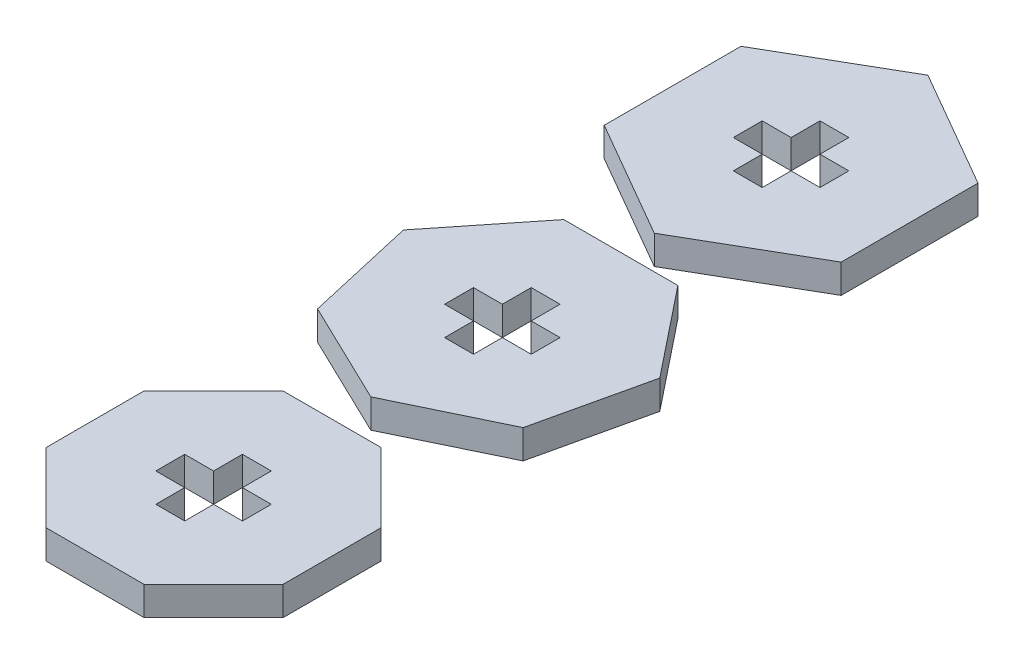
SolidWorks part; units mm, degrees
ref_plane "Front Plane" through (0, 0, 0) normal (0, 0, 1) x (1, 0, 0)
ref_plane "Top Plane" through (0, 0, 0) normal (0, 1, 0) x (1, 0, 0)
ref_plane "Right Plane" through (0, 0, 0) normal (1, 0, 0) x (0, 0, -1)
sketch "Sketch1" plane through (0, 0, 0) normal (0, 1, 0) x (1, 0, 0)
  line L0 (-20.9755, 38.5205) -> (-20.9755, -115.5968) construction
  line L1 (-20.9755, 38.5205) -> (-20.9755, 68.0435) construction
  line L2 (-20.9755, 14.4513) -> (-0.131, 26.4859)
  line L3 (-0.131, 26.4859) -> (-0.131, 50.5551)
  line L4 (-0.131, 50.5551) -> (-20.9755, 62.5897)
  line L5 (-20.9755, 62.5897) -> (-41.82, 50.5551)
  line L6 (-41.82, 50.5551) -> (-41.82, 26.4859)
  line L7 (-41.82, 26.4859) -> (-20.9755, 14.4513)
  line L8 (-20.9755, -35.4152) -> (-2.8873, -26.7044)
  line L9 (-2.8873, -26.7044) -> (1.5801, -7.1313)
  line L10 (1.5801, -7.1313) -> (-10.9373, 8.565)
  line L11 (-10.9373, 8.565) -> (-31.0137, 8.565)
  line L12 (-31.0137, 8.565) -> (-43.5311, -7.1313)
  line L13 (-43.5311, -7.1313) -> (-39.0637, -26.7044)
  line L14 (-39.0637, -26.7044) -> (-20.9755, -35.4152)
  line L15 (-12.3415, -42.235) -> (-29.6096, -42.235)
  line L16 (-29.6096, -42.235) -> (-41.82, -54.4454)
  line L17 (-41.82, -54.4454) -> (-41.82, -71.7136)
  line L18 (-41.82, -71.7136) -> (-29.6096, -83.924)
  line L19 (-29.6096, -83.924) -> (-12.3415, -83.924)
  line L20 (-12.3415, -83.924) -> (-0.131, -71.7136)
  line L21 (-0.131, -71.7136) -> (-0.131, -54.4454)
  line L22 (-0.131, -54.4454) -> (-12.3415, -42.235)
  line L23 (-20.9755, 46.1405) -> (-18.4355, 46.1405)
  line L24 (-130.3452, 38.5205) -> (97.3734, 38.5205) construction
  line L25 (97.3734, -12.2795) -> (-130.3452, -12.2795) construction
  line L26 (-130.3452, -63.0795) -> (97.3734, -63.0795) construction
  line L27 (-18.4355, 46.1405) -> (-18.4355, 41.0605)
  line L28 (-18.4355, 41.0605) -> (-13.3555, 41.0605)
  line L29 (-13.3555, 41.0605) -> (-13.3555, 38.5205)
  line L30 (-13.3555, 38.5205) -> (-13.3555, 35.9805)
  line L31 (-13.3555, 35.9805) -> (-18.4355, 35.9805)
  line L32 (-18.4355, 35.9805) -> (-18.4355, 30.9005)
  line L33 (-18.4355, 30.9005) -> (-20.9755, 30.9005)
  line L34 (-20.9755, 30.9005) -> (-23.5155, 30.9005)
  line L35 (-23.5155, 30.9005) -> (-23.5155, 35.9805)
  line L36 (-23.5155, 35.9805) -> (-28.5955, 35.9805)
  line L37 (-28.5955, 35.9805) -> (-28.5955, 38.5205)
  line L38 (-28.5955, 38.5205) -> (-28.5955, 41.0605)
  line L39 (-28.5955, 41.0605) -> (-23.5155, 41.0605)
  line L40 (-23.5155, 41.0605) -> (-23.5155, 46.1405)
  line L41 (-23.5155, 46.1405) -> (-20.9755, 46.1405)
  line L42 (-23.5155, -14.8195) -> (-28.5955, -14.8195)
  line L43 (-20.9755, -4.6595) -> (-18.4355, -4.6595)
  line L44 (-18.4355, -19.8995) -> (-20.9755, -19.8995)
  line L45 (-23.5155, -9.7395) -> (-23.5155, -4.6595)
  line L46 (-13.3555, -12.2795) -> (-13.3555, -14.8195)
  line L47 (-28.5955, -14.8195) -> (-28.5955, -12.2795)
  line L48 (-18.4355, -4.6595) -> (-18.4355, -9.7395)
  line L49 (-20.9755, -19.8995) -> (-23.5155, -19.8995)
  line L50 (-23.5155, -4.6595) -> (-20.9755, -4.6595)
  line L51 (-13.3555, -14.8195) -> (-18.4355, -14.8195)
  line L52 (-28.5955, -12.2795) -> (-28.5955, -9.7395)
  line L53 (-18.4355, -9.7395) -> (-13.3555, -9.7395)
  line L54 (-23.5155, -19.8995) -> (-23.5155, -14.8195)
  line L55 (-18.4355, -14.8195) -> (-18.4355, -19.8995)
  line L56 (-28.5955, -9.7395) -> (-23.5155, -9.7395)
  line L57 (-13.3555, -9.7395) -> (-13.3555, -12.2795)
  line L58 (-18.4355, -65.6195) -> (-18.4355, -70.6995)
  line L59 (-28.5955, -60.5395) -> (-23.5155, -60.5395)
  line L60 (-13.3555, -60.5395) -> (-13.3555, -63.0795)
  line L61 (-20.9755, -55.4595) -> (-18.4355, -55.4595)
  line L62 (-23.5155, -65.6195) -> (-28.5955, -65.6195)
  line L63 (-18.4355, -70.6995) -> (-20.9755, -70.6995)
  line L64 (-23.5155, -60.5395) -> (-23.5155, -55.4595)
  line L65 (-13.3555, -63.0795) -> (-13.3555, -65.6195)
  line L66 (-18.4355, -55.4595) -> (-18.4355, -60.5395)
  line L67 (-28.5955, -65.6195) -> (-28.5955, -63.0795)
  line L68 (-20.9755, -70.6995) -> (-23.5155, -70.6995)
  line L69 (-23.5155, -55.4595) -> (-20.9755, -55.4595)
  line L70 (-13.3555, -65.6195) -> (-18.4355, -65.6195)
  line L71 (-18.4355, -60.5395) -> (-13.3555, -60.5395)
  line L72 (-28.5955, -63.0795) -> (-28.5955, -60.5395)
  line L73 (-23.5155, -70.6995) -> (-23.5155, -65.6195)
  circle A0 centre (-20.9755, 38.5205) radius 20.8445 construction
  circle A1 centre (-20.9755, -12.2795) radius 20.8445 construction
  circle A2 centre (-20.9755, -63.0795) radius 20.8445 construction
  point P2 (-20.9755, -12.2795)
  point P3 (-20.9755, 38.5205)
  point P4 (-20.9755, -63.0795)
  point P43 (-20.9755, -12.2795)
  point P46 (-20.9755, 38.5205)
  point P52 (-20.9755, 38.5205)
  point P58 (-20.9755, 38.5205)
  point P63 (-20.9755, -12.2795)
  point P64 (-20.9755, 38.5205)
  point P69 (-20.9755, -12.2795)
  point P74 (-20.9755, -12.2795)
  point P78 (-20.9755, -12.2795)
  point P79 (-20.9755, -63.0795)
  point P85 (-20.9755, -63.0795)
  point P90 (-20.9755, -63.0795)
  point P95 (-20.9755, -63.0795)
  point P99 (-20.9755, -63.0795)
  dimension "D3" = 41.689
  dimension "D4" = 41.689
  dimension "D5" = 41.689
  dimension "D1" = 50.8
  dimension "D2" = 50.8
  dimension "D6" = 2.54
  dimension "D7" = 5.08
  dimension "D8" = 5.08
  dimension "D9" = 2.54
  dimension "D11" = 5.08
  dimension "D12" = 5.08
  dimension "D13" = 2.54
  dimension "D14" = 5.08
  dimension "D15" = 5.08
  dimension "D16" = 2.54
  dimension "D10" = 4
extrude "Boss-Extrude1" add sketch "Sketch1" along normal blind 5.08
